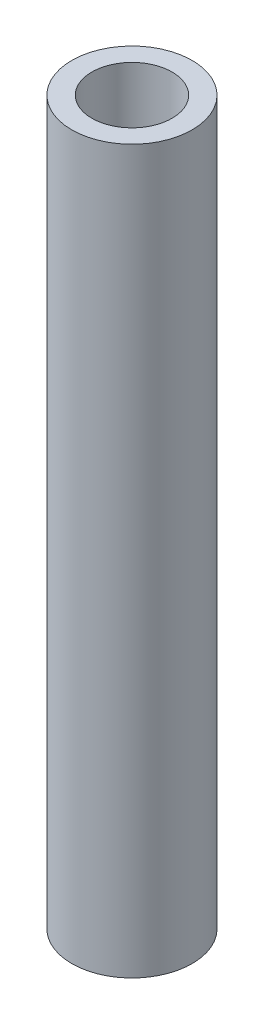
SolidWorks part; units mm, degrees
material "1060 Alloy"
ref_plane "Front Plane" through (0, 0, 0) normal (0, 0, 1) x (1, 0, 0)
ref_plane "Top Plane" through (0, 0, 0) normal (0, 1, 0) x (1, 0, 0)
ref_plane "Right Plane" through (0, 0, 0) normal (1, 0, 0) x (0, 0, -1)
sketch "Sketch1" plane through (0, 0, 0) normal (0, 1, 0) x (1, 0, 0)
  circle A0 centre (0, 0) radius 3
  circle A1 centre (0, 0) radius 4.5
extrude "Boss-Extrude1" add sketch "Sketch1" along normal blind 54
